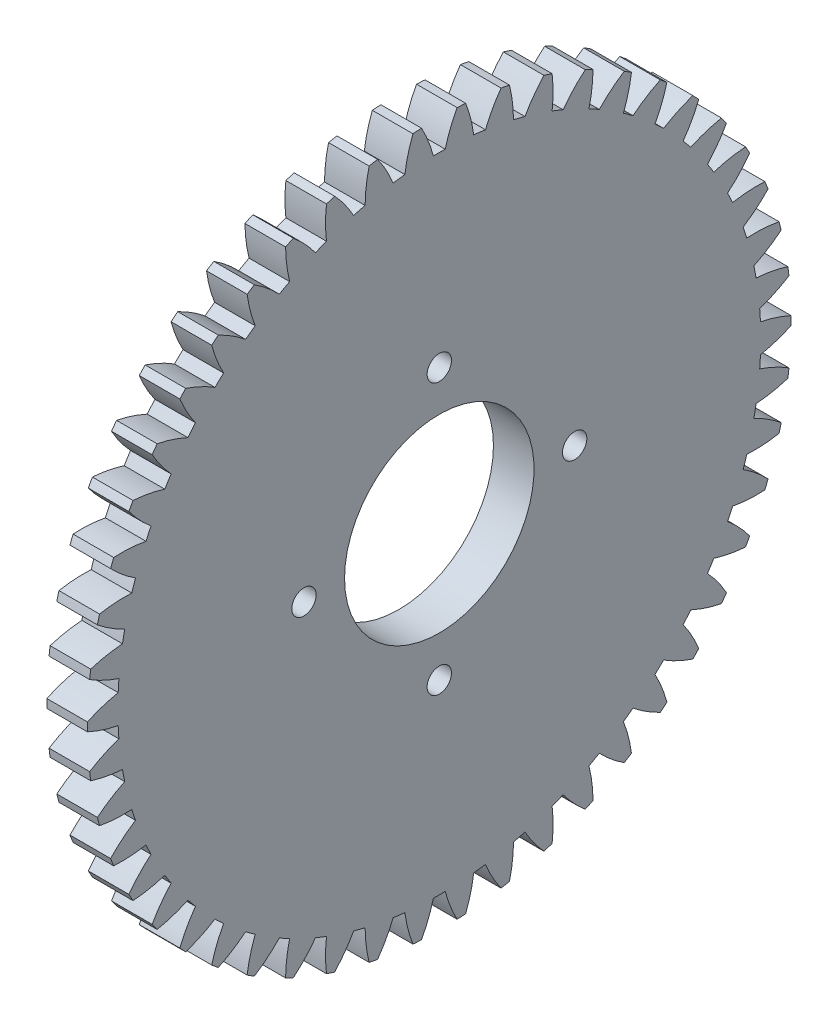
SolidWorks part; units mm, degrees
ref_plane "Plane1" through (0, 0, 0) normal (0, 0, 1) x (1, 0, 0)
ref_plane "Plane2" through (0, 0, 0) normal (0, 1, 0) x (1, 0, 0)
ref_plane "Plane3" through (0, 0, 0) normal (1, 0, 0) x (0, 0, -1)
sketch "HoldingSke" plane through (0, 0, 0) normal (0, 1, 0) x (1, 0, 0)
  line L0 (0, 0) -> (0.6428, -0.766)
  line L1 (-15, 0) -> (100, 0) construction
  line L2 (0, 0) -> (-2.1039, 2.3779)
  line L3 (0, 0) -> (-11.863, 4.5341)
  line L4 (0, 0) -> (5.5511, 6.6156)
  line L5 (0, 0) -> (-46.8476, -17.4728)
  line L6 (0, 0) -> (-2.4869, -1.6779)
  line L7 (-2.1039, 2.3779) -> (8.6586, 51.2059)
  line L8 (-76.2, 54.61) -> (-73.9, 54.61)
  line L9 (-71.009, 38.7566) -> (-53.1078, 45.2721)
  line L10 (-76.2, 71.12) -> (104.1128, 71.12)
  line L11 (0, 0) -> (-3, 0)
  line L12 (-76.2, 101.6) -> (-76.162, 101.6)
  line L13 (24.9733, 27.94) -> (52.9518, 28.4284)
  line L14 (24.9733, 27.94) -> (24.9743, 27.94)
  line L15 (24.9733, 27.94) -> (100.4006, 29.5858)
  line L16 (-63.627, -1) -> (-12.827, -1)
  circle A0 centre (0, 0) radius 7
  circle A1 centre (0, 0) radius 0.5
  circle A2 centre (0, 0) radius 0.5
  circle A3 centre (0, 0) radius 7
  dimension "MHD" = 1
  dimension "Hub_dia" = 1
  dimension "Bore" = 14
  dimension "MBD" = 14
  dimension "Num_teeth" = 50
  dimension "Pitch" = 1
  dimension "Overall_len" = 50
  dimension "Show_teeth" = 50
  dimension "Thickness" = 3
  dimension "OAL" = 50.0001
  dimension "T_dim" = 2.3
  dimension "Ap" = 20
  dimension "H" = 19.05
  dimension "Pitch_radius" = 180.3128
  dimension "Width" = 3
  dimension "Backlash" = 0.038
  dimension "Addendum_fac" = 1
  dimension "Dedendum_fac" = 1.25
  dimension "Clearance_fac" = 0.25
  dimension "Dedendum_add" = 0.001
  dimension "Module" = 1
sketch "BasProSke" plane through (0, 0, 0) normal (0, 1, 0) x (1, 0, 0)
  line L0 (-10, 0) -> (60, 0) construction
  line L1 (0, 0) -> (0, 26)
  line L2 (0, 0) -> (3, 0)
  line L3 (3, 0) -> (3, 26)
  line L4 (3, 26) -> (0, 26)
  dimension "Thickness" = 3
  dimension "Diameter" = 52
revolve "Base-Revolve" add sketch "BasProSke" angle 360 about L0
sketch "TooCutSke" plane through (0, 0, 0) normal (1, 0, 0) x (0, 0, -1)
  line L1 (0, 0) -> (0, 107) construction
  line L2 (0, 0) -> (-0.8518, 24.9855) construction
  line L3 (0, 0) -> (-3.1382, 49.8807) construction
  line L4 (-0.8518, 24.9855) -> (-1.5691, 24.9404) construction
  arc A0 (0.4377, 23.745) -> (-0.4377, 23.745) centre (0, 0) ccw
  arc A1 (1.3294, 25.9914) -> (-1.3294, 25.9914) centre (0, 0) ccw
  circle A2 centre (0, 0) radius 25 construction
  circle A3 centre (0, 0) radius 23.4923 construction
  arc A4 (-0.4377, 23.745) -> (-1.3294, 25.9914) centre (-10.1099, 21.2056) ccw
  arc A5 (1.3294, 25.9914) -> (0.4377, 23.745) centre (10.1099, 21.2056) ccw
  dimension "Root_dia" = 47.498
  dimension "Overcut_dia" = 52.0508
  dimension "Pitch_dia" = 50
  dimension "Base_dia" = 46.9846
  dimension "Flank_rad" = 10
  dimension "Half_ang" = 3.6
  dimension "Half_CT" = 0.7188
extrude "ToothCut" cut sketch "TooCutSke" along normal through all
fillet "Breaks" [suppressed] radius 0.02
fillet "RootFillets" [suppressed] radius 0.251
pattern_circular "TeethCuts" count 50 every 7.2 about axis through (-10, 0, 0) along (1, 0, 0) of "ToothCut", "RootFillets", "Breaks"
sketch "HubNeaOneSke" plane through (0, 0, 0) normal (-1, 0, 0) x (0, 0, 1)
  circle A0 centre (0, 0) radius 0.5
  dimension "Diameter" = 1
extrude "HubNearOne" [suppressed] add sketch "HubNeaOneSke" along normal blind 47.0001
sketch "HubNeaBotSke" plane through (0, 0, 0) normal (-1, 0, 0) x (0, 0, 1)
  circle A0 centre (0, 0) radius 0.5
  dimension "Diameter" = 1
extrude "HubNearBoth" add sketch "HubNeaBotSke" along normal blind 23.5
ref_plane "FarPln" through (3, 0, 0) normal (1, 0, 0) x (0, 0, -1)
sketch "HubFarSke" plane through (3, 0, 0) normal (1, 0, 0) x (0, 0, -1)
  circle A0 centre (0, 0) radius 0.5
  dimension "Diameter" = 1
extrude "HubFar" add sketch "HubFarSke" along normal blind 23.5
sketch "BorSke" plane through (0, 0, 0) normal (1, 0, 0) x (0, 0, -1)
  circle A0 centre (0, 0) radius 7
  dimension "Diameter" = 14
extrude "Bore" cut sketch "BorSke" along normal mid plane 100.0001
sketch "KeySke" plane through (0, 0, 0) normal (1, 0, 0) x (0, 0, -1)
  line L0 (-2.5, 0) -> (-2.5, 9.3)
  line L1 (-2.5, 9.3) -> (2.5, 9.3)
  line L2 (2.5, 9.3) -> (2.5, 0)
  line L3 (0, 0) -> (0, 34) construction
  line L4 (-2.5, 0) -> (2.5, 0)
  dimension "Offset" = 9.3
  dimension "Width" = 5
extrude "Keyway" [suppressed] cut sketch "KeySke" along normal mid plane 100.0001
pattern_circular "Keyway2" [suppressed] count 2 every 90 about axis through (-10, 0, 0) along (1, 0, 0)
sketch "Sketch1" plane through (3, 0, 0) normal (1, 0, 0) x (0, 0, -1)
  line L0 (0, 0) -> (0, -10) construction
  circle A0 centre (0, -10) radius 0.9
  circle A1 centre (-10, 0) radius 0.9
  circle A2 centre (0, 10) radius 0.9
  circle A3 centre (10, 0) radius 0.9
  point P13 (0, 0)
  dimension "D2" = 4
  dimension "D1" = 10
extrude "Cut-Extrude1" cut sketch "Sketch1" against normal blind 3
equation "' \"Module@HoldingSke\" = 6.35"
equation "' \"Num_teeth@HoldingSke\" = 12"
equation "' \"Ap@HoldingSke\" =  20"
equation "' \"Ap@HoldingSke\" = 20"
equation "' \"Width@HoldingSke\" = 0.5 * 25.4"
equation "' \"Hub_dia@HoldingSke\"= 1 * 25.4"
equation "' \"Hub_dia@HoldingSke\" = 1 * 25.4"
equation "' \"Overall_len@HoldingSke\" = 1.0 * 25.4"
equation "' \"Bore@HoldingSke\" = 0.75 * 25.4"
equation "' \"T_dim@HoldingSke\" = 0.1 * 25.4"
equation "' \"Width@KeySke\" = 0.25 * 25.4"
equation "' \"Show_teeth@HoldingSke\" = 13"
equation "' \"Backlash@HoldingSke\" = 0.009 * 25.4"
equation "' \"Addendum_fac@HoldingSke\" = 1.0"
equation "' \"Dedendum_fac@HoldingSke\" = 1.25"
equation "' \"Dedendum_add@HoldingSke\" = 0.00005 * 25.4"
equation "' \"Clearance_fac@HoldingSke\" = 0.25"
equation "\"Pitch@HoldingSke\" = 1 / \"Module@HoldingSke\""
equation "\"Overcut_dia@TooCutSke\" = (\"Num_teeth@HoldingSke\" + 2 * \"Addendum_fac@HoldingSke\") / \"Pitch@HoldingSke\" + 0.002 * 25.4"
equation "\"Pitch_dia@TooCutSke\" = \"Num_teeth@HoldingSke\" / \"Pitch@HoldingSke\""
equation "\"Base_dia@TooCutSke\" = \"Num_teeth@HoldingSke\" / \"Pitch@HoldingSke\" * cos((\"Ap@HoldingSke\"  * 3.14159265 / 180))"
equation "\"Root_dia@TooCutSke\" = (\"Num_teeth@HoldingSke\" + 2) / \"Pitch@HoldingSke\" - 2 * (\"Addendum_fac@HoldingSke\" + \"Dedendum_fac@HoldingSke\") / \"Pitch@HoldingSke\" - \"Dedendum_add@HoldingSke\" * 2"
equation "\"Half_ang@TooCutSke\" = 180 / \"Num_teeth@HoldingSke\""
equation "\"Half_CT@TooCutSke\" = \"Num_teeth@HoldingSke\" / \"Pitch@HoldingSke\" * sin((3.14159265 / 2 / \"Num_teeth@HoldingSke\")) / 2 - 7 * \"Backlash@HoldingSke\" / 4"
equation "\"Flank_rad@TooCutSke\" = \"Num_teeth@HoldingSke\" / \"Pitch@HoldingSke\" / 5"
equation "\"Radius@RootFillets\" = \"Clearance_fac@HoldingSke\" / \"Pitch@HoldingSke\" + \"Dedendum_add@HoldingSke\""
equation "\"Break_rad@Breaks\" = 0.02 / \"Pitch@HoldingSke\""
equation "\"Thickness@HoldingSke\" = \"Width@HoldingSke\""
equation "\"OAL@HoldingSke\" = \"Thickness@HoldingSke\""
equation "\"MHD@HoldingSke\" = (\"Num_teeth@HoldingSke\" + 2) / \"Pitch@HoldingSke\" - 2 * (\"Addendum_fac@HoldingSke\" + \"Dedendum_fac@HoldingSke\")  / \"Pitch@HoldingSke\" - \"Dedendum_add@HoldingSke\" * 2"
equation "\"MBD@HoldingSke\" = (\"Num_teeth@HoldingSke\" + 2) / \"Pitch@HoldingSke\" - 2 * (\"Addendum_fac@HoldingSke\" + \"Dedendum_fac@HoldingSke\")  / \"Pitch@HoldingSke\" - \"Dedendum_add@HoldingSke\" * 2 - 0.002 * 25.4"
equation "\"MHD@HoldingSke\" = ((sgn( \"MHD@HoldingSke\" - \"Hub_dia@HoldingSke\" )-1)*( \"MHD@HoldingSke\" - \"Hub_dia@HoldingSke\" ))/-2+ \"Hub_dia@HoldingSke\""
equation "\"MBD@HoldingSke\" = ((sgn( \"MBD@HoldingSke\" - \"Bore@HoldingSke\" )-1)*( \"MBD@HoldingSke\" - \"Bore@HoldingSke\" ))/-2+ \"Bore@HoldingSke\""
equation "\"OAL@HoldingSke\" = ((sgn( \"OAL@HoldingSke\" - \"Overall_len@HoldingSke\" )+1)*( \"OAL@HoldingSke\" - \"Overall_len@HoldingSke\" ))/2 + \"Overall_len@HoldingSke\" + 0.000002 * 25.4"
equation "\"Num_teeth@TeethCuts\" = int( \"Show_teeth@HoldingSke\" ) + 1"
equation "\"Num_teeth@TeethCuts\" = ((sgn( \"Num_teeth@TeethCuts\" - \"Num_teeth@HoldingSke\" )-1)*( \"Num_teeth@TeethCuts\" - \"Num_teeth@HoldingSke\" ))/-2+ \"Num_teeth@HoldingSke\""
equation "\"Num_teeth@TeethCuts\" = ((sgn( \"Num_teeth@TeethCuts\" - 2.0)+1)*( \"Num_teeth@TeethCuts\" - 2.0))/2 +2.0"
equation "\"Angle@TeethCuts\" = 360.0 / \"Num_teeth@HoldingSke\""
equation "\"Diameter@BasProSke\" = (\"Num_teeth@HoldingSke\" + 2 * \"Addendum_fac@HoldingSke\") / \"Pitch@HoldingSke\""
equation "\"Thickness@BasProSke\"  = \"Thickness@HoldingSke\""
equation "' \"Fillet_rad@BasProSke\" =  \"Thickness@HoldingSke\" * 0.05"
equation "' \"Fillet_rad@BasProSke\" = \"Thickness@HoldingSke\" * 0.05"
equation "\"MHD@HoldingSke\" = ((sgn( \"MHD@HoldingSke\" - \"Root_dia@TooCutSke\" )-1)*( \"MHD@HoldingSke\" - \"Root_dia@TooCutSke\" ))/-2+ \"Root_dia@TooCutSke\""
equation "\"Diameter@HubNeaOneSke\" = \"MHD@HoldingSke\""
equation "\"Length@HubNearOne\" = \"OAL@HoldingSke\" - \"Thickness@BasProSke\""
equation "\"Diameter@HubNeaBotSke\" = \"MHD@HoldingSke\""
equation "\"Length@HubNearBoth\" = ( \"OAL@HoldingSke\" - \"Thickness@BasProSke\" ) / 2.0"
equation "\"Thickness@FarPln\" = \"Thickness@BasProSke\""
equation "\"Diameter@HubFarSke\" = \"MHD@HoldingSke\""
equation "\"Length@HubFar\" = ( \"OAL@HoldingSke\" - \"Thickness@BasProSke\" ) / 2.0"
equation "\"Diameter@BorSke\" = \"MBD@HoldingSke\""
equation "\"D1@Bore\" = \"OAL@HoldingSke\" * 2.0"
equation "\"D1@Keyway\" = \"OAL@HoldingSke\" * 2.0"
equation "\"Offset@KeySke\" = \"T_dim@HoldingSke\" + \"MBD@HoldingSke\" / 2.0"
